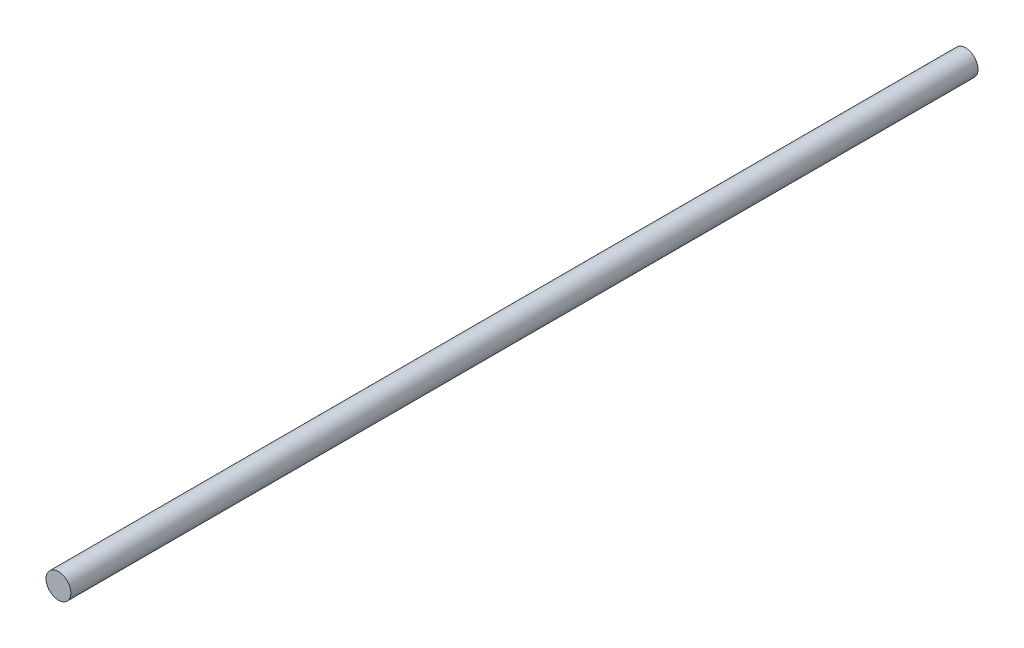
SolidWorks part; units mm, degrees
ref_plane "前视基准面" through (0, 0, 0) normal (0, 0, 1) x (1, 0, 0)
ref_plane "上视基准面" through (0, 0, 0) normal (0, 1, 0) x (1, 0, 0)
ref_plane "右视基准面" through (0, 0, 0) normal (1, 0, 0) x (0, 0, -1)
sketch "草图1" plane through (0, 0, 0) normal (0, 0, 1) x (1, 0, 0)
  circle A0 centre (0, 0) radius 10
  dimension "D1" = 20
extrude "凸台-拉伸1" add sketch "草图1" along normal blind 730
